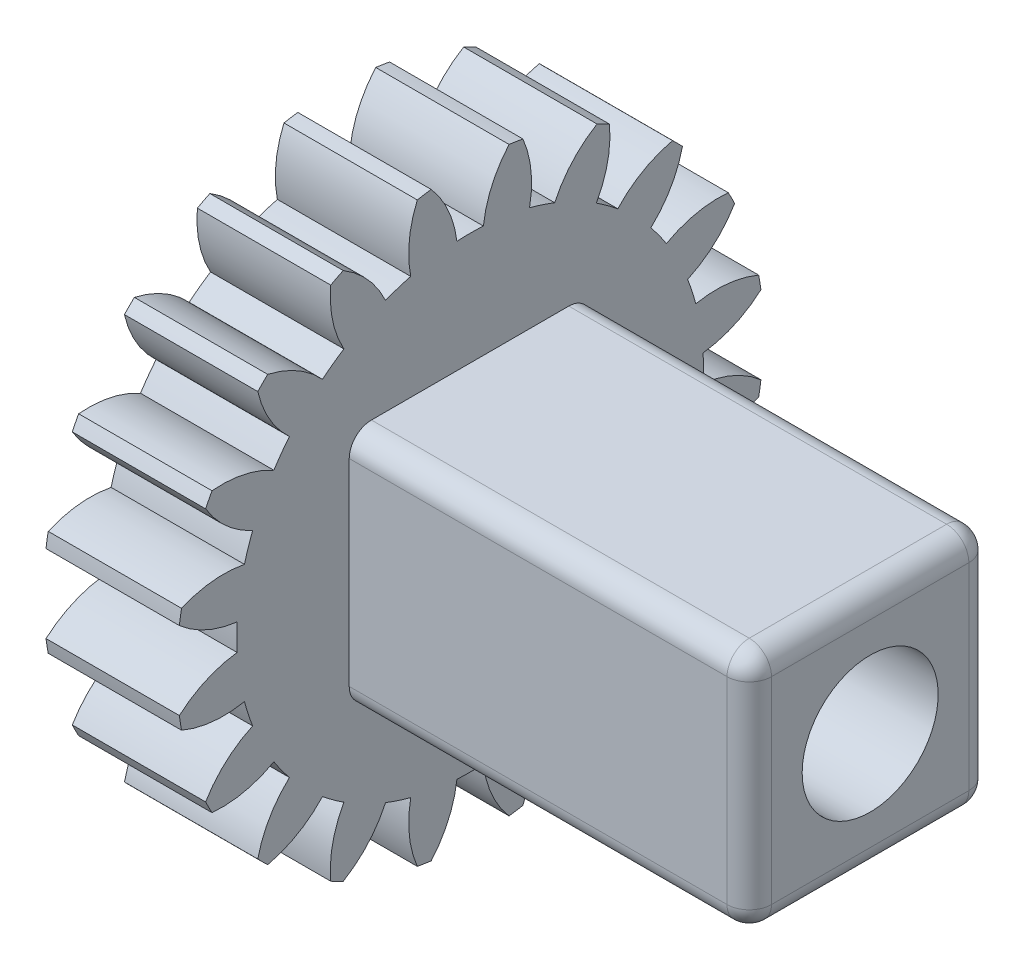
SolidWorks part; units mm, degrees
material "Custom Plastic"
ref_plane "Plane1" through (0, 0, 0) normal (0, 0, 1) x (1, 0, 0)
ref_plane "Plane2" through (0, 0, 0) normal (0, 1, 0) x (1, 0, 0)
ref_plane "Plane3" through (0, 0, 0) normal (1, 0, 0) x (0, 0, -1)
other "Configuration Table"
sketch "HoldingSke" plane through (0, 0, 0) normal (0, 1, 0) x (1, 0, 0)
  line L0 (0, 0) -> (0.3132, -0.114)
  line L1 (-15, 0) -> (100, 0) construction
  line L2 (0, 0) -> (-2.1039, 2.3779)
  line L3 (0, 0) -> (-11.863, 4.5341)
  line L4 (0, 0) -> (8.1152, 2.9537)
  line L5 (0, 0) -> (-46.8476, -17.4728)
  line L6 (0, 0) -> (-12.4344, -8.3896)
  line L7 (-2.1039, 2.3779) -> (8.6586, 51.2059)
  line L8 (-76.2, 54.61) -> (-75.5, 54.61)
  line L9 (-71.009, 38.7566) -> (-53.1078, 45.2721)
  line L10 (-76.2, 71.12) -> (104.1128, 71.12)
  line L11 (0, 0) -> (-15, 0)
  line L12 (-76.2, 101.6) -> (-76.093, 101.6)
  line L13 (24.9733, 27.94) -> (52.9518, 28.4284)
  line L14 (24.9733, 27.94) -> (24.9743, 27.94)
  line L15 (24.9733, 27.94) -> (100.4006, 29.5858)
  line L16 (-63.627, -3) -> (-12.827, -3)
  circle A0 centre (0, 0) radius 2
  circle A1 centre (0, 0) radius 26.249
  circle A2 centre (0, 0) radius 37.5
  circle A3 centre (0, 0) radius 2
  dimension "MHD" = 52.498
  dimension "Hub_dia" = 75
  dimension "Bore" = 4
  dimension "MBD" = 4
  dimension "Num_teeth" = 20
  dimension "Pitch" = 0.3333
  dimension "Overall_len" = 50
  dimension "Show_teeth" = 20
  dimension "Thickness" = 15
  dimension "OAL" = 50.0001
  dimension "T_dim" = 0.7
  dimension "Ap" = 20
  dimension "H" = 19.05
  dimension "Pitch_radius" = 180.3128
  dimension "Width" = 15
  dimension "Backlash" = 0.107
  dimension "Addendum_fac" = 1
  dimension "Dedendum_fac" = 1.25
  dimension "Clearance_fac" = 0.25
  dimension "Dedendum_add" = 0.001
  dimension "Module" = 3
sketch "BasProSke" plane through (0, 0, 0) normal (0, 1, 0) x (1, 0, 0)
  line L0 (-10, 0) -> (60, 0) construction
  line L1 (0, 0) -> (0, 33)
  line L2 (0, 0) -> (15, 0)
  line L3 (15, 0) -> (15, 33)
  line L4 (15, 33) -> (0, 33)
  dimension "Thickness" = 15
  dimension "Diameter" = 66
revolve "Base-Revolve" add sketch "BasProSke" angle 360 about L0
sketch "TooCutSke" plane through (0, 0, 0) normal (1, 0, 0) x (0, 0, -1)
  line L1 (0, 0) -> (0, 107) construction
  line L2 (0, 0) -> (-2.5409, 29.8922) construction
  line L3 (0, 0) -> (-9.3616, 59.1066) construction
  line L4 (-2.5409, 29.8922) -> (-4.6808, 29.5533) construction
  arc A0 (1.4893, 26.2067) -> (-1.4893, 26.2067) centre (0, 0) ccw
  arc A1 (4.4016, 32.7308) -> (-4.4016, 32.7308) centre (0, 0) ccw
  circle A2 centre (0, 0) radius 30 construction
  circle A3 centre (0, 0) radius 28.1908 construction
  arc A4 (-1.4893, 26.2067) -> (-4.4016, 32.7308) centre (-13.4064, 24.799) ccw
  arc A5 (4.4016, 32.7308) -> (1.4893, 26.2067) centre (13.4064, 24.799) ccw
  dimension "Root_dia" = 52.498
  dimension "Overcut_dia" = 66.0508
  dimension "Pitch_dia" = 60
  dimension "Base_dia" = 56.3816
  dimension "Flank_rad" = 12
  dimension "Half_ang" = 9
  dimension "Half_CT" = 2.1665
extrude "ToothCut" cut sketch "TooCutSke" along normal through all
fillet "Breaks" [suppressed] radius 0.06
fillet "RootFillets" [suppressed] radius 0.751
pattern_circular "TeethCuts" count 20 every 18 about axis through (-10, 0, 0) along (1, 0, 0) of "ToothCut", "RootFillets", "Breaks"
sketch "HubNeaOneSke" plane through (0, 0, 0) normal (-1, 0, 0) x (0, 0, 1)
  circle A0 centre (0, 0) radius 26.249
  dimension "Diameter" = 52.498
extrude "HubNearOne" [suppressed] add sketch "HubNeaOneSke" along normal blind 35.0001
sketch "HubNeaBotSke" plane through (0, 0, 0) normal (-1, 0, 0) x (0, 0, 1)
  circle A0 centre (0, 0) radius 26.249
  dimension "Diameter" = 52.498
extrude "HubNearBoth" [suppressed] add sketch "HubNeaBotSke" along normal blind 17.5
ref_plane "FarPln" through (15, 0, 0) normal (1, 0, 0) x (0, 0, -1)
sketch "HubFarSke" plane through (15, 0, 0) normal (1, 0, 0) x (0, 0, -1)
  circle A0 centre (0, 0) radius 26.249
  dimension "Diameter" = 52.498
extrude "HubFar" [suppressed] add sketch "HubFarSke" along normal blind 17.5
sketch "BorSke" plane through (0, 0, 0) normal (1, 0, 0) x (0, 0, -1)
  circle A0 centre (0, 0) radius 2
  dimension "Diameter" = 4
extrude "Bore" cut sketch "BorSke" along normal mid plane 100.0001
sketch "KeySke" plane through (0, 0, 0) normal (1, 0, 0) x (0, 0, -1)
  line L0 (-0.8, 0) -> (-0.8, 2.7)
  line L1 (-0.8, 2.7) -> (0.8, 2.7)
  line L2 (0.8, 2.7) -> (0.8, 0)
  line L3 (0, 0) -> (0, 34) construction
  line L4 (-0.8, 0) -> (0.8, 0)
  dimension "Offset" = 2.7
  dimension "Width" = 1.6
extrude "Keyway" [suppressed] cut sketch "KeySke" along normal mid plane 100.0001
pattern_circular "Keyway2" [suppressed] count 2 every 90 about axis through (-10, 0, 0) along (1, 0, 0)
sketch "Sketch1" plane through (15, 0, 0) normal (1, 0, 0) x (0, 0, -1)
  line L0 (-13.6, 13.6) -> (13.6, -13.6) construction
  line L1 (-13.6, 13.6) -> (13.6, 13.6)
  line L2 (-13.6, 13.6) -> (-13.6, -13.6)
  line L3 (-13.6, -13.6) -> (13.6, -13.6)
  line L4 (13.6, 13.6) -> (13.6, -13.6)
  point P4 (0, 0)
  dimension "D1" = 27.2
extrude "Boss-Extrude1" add sketch "Sketch1" along normal blind 45
sketch "Sketch2" plane through (0, 0, 0) normal (-1, 0, 0) x (0, 0, 1)
  circle A0 centre (0, 0) radius 7.65
  dimension "D1" = 15.3
extrude "Cut-Extrude1" cut sketch "Sketch2" against normal up to surface (60 mm away) contours A0 up to face at (60, 0, 0)
fillet "Fillet2" radius 2.5 8 edges at (60, 13.6, 0) (60, 0, 13.6) (60, -13.6, 0) (60, 0, -13.6) (37.5, -13.6, -13.6) (37.5, 13.6, -13.6) (37.5, 13.6, 13.6) (37.5, -13.6, 13.6)
equation "' \"Module@HoldingSke\" = 6.35"
equation "' \"Num_teeth@HoldingSke\" = 12"
equation "' \"Ap@HoldingSke\" =  20"
equation "' \"Ap@HoldingSke\" = 20"
equation "' \"Width@HoldingSke\" = 0.5 * 25.4"
equation "' \"Hub_dia@HoldingSke\"= 1 * 25.4"
equation "' \"Hub_dia@HoldingSke\" = 1 * 25.4"
equation "' \"Overall_len@HoldingSke\" = 1.0 * 25.4"
equation "' \"Bore@HoldingSke\" = 0.75 * 25.4"
equation "' \"T_dim@HoldingSke\" = 0.1 * 25.4"
equation "' \"Width@KeySke\" = 0.25 * 25.4"
equation "' \"Show_teeth@HoldingSke\" = 13"
equation "' \"Backlash@HoldingSke\" = 0.009 * 25.4"
equation "' \"Addendum_fac@HoldingSke\" = 1.0"
equation "' \"Dedendum_fac@HoldingSke\" = 1.25"
equation "' \"Dedendum_add@HoldingSke\" = 0.00005 * 25.4"
equation "' \"Clearance_fac@HoldingSke\" = 0.25"
equation "\"Pitch@HoldingSke\" = 1 / \"Module@HoldingSke\""
equation "\"Overcut_dia@TooCutSke\" = (\"Num_teeth@HoldingSke\" + 2 * \"Addendum_fac@HoldingSke\") / \"Pitch@HoldingSke\" + 0.002 * 25.4"
equation "\"Pitch_dia@TooCutSke\" = \"Num_teeth@HoldingSke\" / \"Pitch@HoldingSke\""
equation "\"Base_dia@TooCutSke\" = \"Num_teeth@HoldingSke\" / \"Pitch@HoldingSke\" * cos((\"Ap@HoldingSke\"  * 3.14159265 / 180))"
equation "\"Root_dia@TooCutSke\" = (\"Num_teeth@HoldingSke\" + 2) / \"Pitch@HoldingSke\" - 2 * (\"Addendum_fac@HoldingSke\" + \"Dedendum_fac@HoldingSke\") / \"Pitch@HoldingSke\" - \"Dedendum_add@HoldingSke\" * 2"
equation "\"Half_ang@TooCutSke\" = 180 / \"Num_teeth@HoldingSke\""
equation "\"Half_CT@TooCutSke\" = \"Num_teeth@HoldingSke\" / \"Pitch@HoldingSke\" * sin((3.14159265 / 2 / \"Num_teeth@HoldingSke\")) / 2 - 7 * \"Backlash@HoldingSke\" / 4"
equation "\"Flank_rad@TooCutSke\" = \"Num_teeth@HoldingSke\" / \"Pitch@HoldingSke\" / 5"
equation "\"Radius@RootFillets\" = \"Clearance_fac@HoldingSke\" / \"Pitch@HoldingSke\" + \"Dedendum_add@HoldingSke\""
equation "\"Break_rad@Breaks\" = 0.02 / \"Pitch@HoldingSke\""
equation "\"Thickness@HoldingSke\" = \"Width@HoldingSke\""
equation "\"OAL@HoldingSke\" = \"Thickness@HoldingSke\""
equation "\"MHD@HoldingSke\" = (\"Num_teeth@HoldingSke\" + 2) / \"Pitch@HoldingSke\" - 2 * (\"Addendum_fac@HoldingSke\" + \"Dedendum_fac@HoldingSke\")  / \"Pitch@HoldingSke\" - \"Dedendum_add@HoldingSke\" * 2"
equation "\"MBD@HoldingSke\" = (\"Num_teeth@HoldingSke\" + 2) / \"Pitch@HoldingSke\" - 2 * (\"Addendum_fac@HoldingSke\" + \"Dedendum_fac@HoldingSke\")  / \"Pitch@HoldingSke\" - \"Dedendum_add@HoldingSke\" * 2 - 0.002 * 25.4"
equation "\"MHD@HoldingSke\" = ((sgn( \"MHD@HoldingSke\" - \"Hub_dia@HoldingSke\" )-1)*( \"MHD@HoldingSke\" - \"Hub_dia@HoldingSke\" ))/-2+ \"Hub_dia@HoldingSke\""
equation "\"MBD@HoldingSke\" = ((sgn( \"MBD@HoldingSke\" - \"Bore@HoldingSke\" )-1)*( \"MBD@HoldingSke\" - \"Bore@HoldingSke\" ))/-2+ \"Bore@HoldingSke\""
equation "\"OAL@HoldingSke\" = ((sgn( \"OAL@HoldingSke\" - \"Overall_len@HoldingSke\" )+1)*( \"OAL@HoldingSke\" - \"Overall_len@HoldingSke\" ))/2 + \"Overall_len@HoldingSke\" + 0.000002 * 25.4"
equation "\"Num_teeth@TeethCuts\" = int( \"Show_teeth@HoldingSke\" ) + 1"
equation "\"Num_teeth@TeethCuts\" = ((sgn( \"Num_teeth@TeethCuts\" - \"Num_teeth@HoldingSke\" )-1)*( \"Num_teeth@TeethCuts\" - \"Num_teeth@HoldingSke\" ))/-2+ \"Num_teeth@HoldingSke\""
equation "\"Num_teeth@TeethCuts\" = ((sgn( \"Num_teeth@TeethCuts\" - 2.0)+1)*( \"Num_teeth@TeethCuts\" - 2.0))/2 +2.0"
equation "\"Angle@TeethCuts\" = 360.0 / \"Num_teeth@HoldingSke\""
equation "\"Diameter@BasProSke\" = (\"Num_teeth@HoldingSke\" + 2 * \"Addendum_fac@HoldingSke\") / \"Pitch@HoldingSke\""
equation "\"Thickness@BasProSke\"  = \"Thickness@HoldingSke\""
equation "' \"Fillet_rad@BasProSke\" =  \"Thickness@HoldingSke\" * 0.05"
equation "' \"Fillet_rad@BasProSke\" = \"Thickness@HoldingSke\" * 0.05"
equation "\"MHD@HoldingSke\" = ((sgn( \"MHD@HoldingSke\" - \"Root_dia@TooCutSke\" )-1)*( \"MHD@HoldingSke\" - \"Root_dia@TooCutSke\" ))/-2+ \"Root_dia@TooCutSke\""
equation "\"Diameter@HubNeaOneSke\" = \"MHD@HoldingSke\""
equation "\"Length@HubNearOne\" = \"OAL@HoldingSke\" - \"Thickness@BasProSke\""
equation "\"Diameter@HubNeaBotSke\" = \"MHD@HoldingSke\""
equation "\"Length@HubNearBoth\" = ( \"OAL@HoldingSke\" - \"Thickness@BasProSke\" ) / 2.0"
equation "\"Thickness@FarPln\" = \"Thickness@BasProSke\""
equation "\"Diameter@HubFarSke\" = \"MHD@HoldingSke\""
equation "\"Length@HubFar\" = ( \"OAL@HoldingSke\" - \"Thickness@BasProSke\" ) / 2.0"
equation "\"Diameter@BorSke\" = \"MBD@HoldingSke\""
equation "\"D1@Bore\" = \"OAL@HoldingSke\" * 2.0"
equation "\"D1@Keyway\" = \"OAL@HoldingSke\" * 2.0"
equation "\"Offset@KeySke\" = \"T_dim@HoldingSke\" + \"MBD@HoldingSke\" / 2.0"
